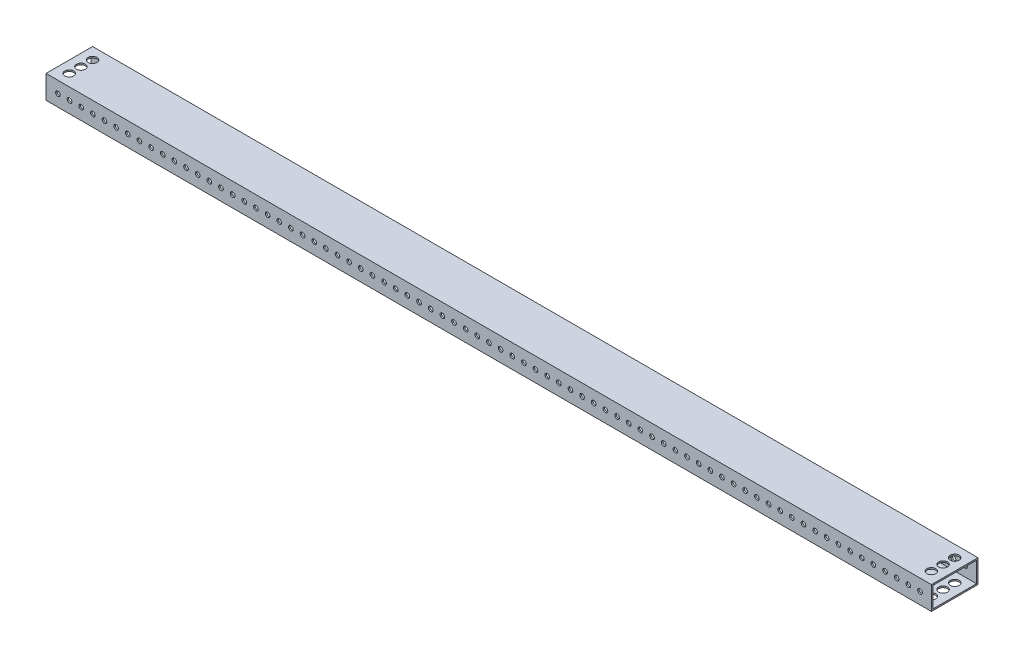
SolidWorks part; units mm, degrees
ref_plane "Front Plane" through (0, 0, 0) normal (0, 0, 1) x (1, 0, 0)
ref_plane "Top Plane" through (0, 0, 0) normal (0, 1, 0) x (1, 0, 0)
ref_plane "Right Plane" through (0, 0, 0) normal (1, 0, 0) x (0, 0, -1)
sketch "Sketch1" plane through (0, 0, 0) normal (0, 1, 0) x (1, 0, 0)
  line L1 (482.6, 25.4) -> (-482.6, 25.4)
  line L2 (482.6, 25.4) -> (482.6, -25.4)
  line L3 (482.6, -25.4) -> (-482.6, -25.4)
  line L4 (-482.6, 25.4) -> (-482.6, -25.4)
  line L5 (482.6, 25.4) -> (-482.6, -25.4) construction
  line L6 (482.6, -25.4) -> (-482.6, 25.4) construction
  point P0 (0, 0)
  dimension "D1" = 50.8
  dimension "D2" = 965.2
extrude "Boss-Extrude1" add sketch "Sketch1" along normal blind 25.4
sketch "Sketch2" plane through (-482.6, 0, 0) normal (-1, 0, 0) x (0, 0, 1)
  line L1 (23.7937, 23.7836) -> (-23.7836, 23.7836)
  line L2 (23.7937, 23.7836) -> (23.7937, 1.6265)
  line L3 (23.7937, 1.6265) -> (-23.7836, 1.6265)
  line L4 (-23.7836, 23.7836) -> (-23.7836, 1.6265)
  line L6 (-25.4, 25.4) -> (-25.4, 0) construction
  line L7 (25.4, 25.4) -> (25.4, 0) construction
  dimension "D1" = 2.286
  dimension "D2" = 2.286
  dimension "D3" = 1.6164
  dimension "D4" = 1.6063
extrude "Cut-Extrude1" cut sketch "Sketch2" against normal through all
sketch "Sketch3" plane through (0, 0, 25.4) normal (0, 0, 1) x (1, 0, 0)
  line L0 (-1393.7901, 12.7) -> (48606.2099, 12.7) construction
  line L1 (-482.6, 25.4) -> (-482.6, 0) construction
  circle A1 centre (-469.646, 12.7) radius 2.54
  circle A2 centre (-456.946, 12.7) radius 2.54
  circle A3 centre (-444.246, 12.7) radius 2.54
  circle A4 centre (-431.546, 12.7) radius 2.54
  circle A5 centre (-418.846, 12.7) radius 2.54
  circle A6 centre (-406.146, 12.7) radius 2.54
  circle A7 centre (-393.446, 12.7) radius 2.54
  circle A8 centre (-380.746, 12.7) radius 2.54
  circle A9 centre (-368.046, 12.7) radius 2.54
  circle A10 centre (-355.346, 12.7) radius 2.54
  circle A11 centre (-342.646, 12.7) radius 2.54
  circle A12 centre (-329.946, 12.7) radius 2.54
  circle A13 centre (-317.246, 12.7) radius 2.54
  circle A14 centre (-304.546, 12.7) radius 2.54
  circle A15 centre (-291.846, 12.7) radius 2.54
  circle A16 centre (-279.146, 12.7) radius 2.54
  circle A17 centre (-266.446, 12.7) radius 2.54
  circle A18 centre (-253.746, 12.7) radius 2.54
  circle A19 centre (-241.046, 12.7) radius 2.54
  circle A20 centre (-228.346, 12.7) radius 2.54
  circle A21 centre (-215.646, 12.7) radius 2.54
  circle A22 centre (-202.946, 12.7) radius 2.54
  circle A23 centre (-190.246, 12.7) radius 2.54
  circle A24 centre (-177.546, 12.7) radius 2.54
  circle A25 centre (-164.846, 12.7) radius 2.54
  circle A26 centre (-152.146, 12.7) radius 2.54
  circle A27 centre (-139.446, 12.7) radius 2.54
  circle A28 centre (-126.746, 12.7) radius 2.54
  circle A29 centre (-114.046, 12.7) radius 2.54
  circle A30 centre (-101.346, 12.7) radius 2.54
  circle A31 centre (-88.646, 12.7) radius 2.54
  circle A32 centre (-75.946, 12.7) radius 2.54
  circle A33 centre (-63.246, 12.7) radius 2.54
  circle A34 centre (-50.546, 12.7) radius 2.54
  circle A35 centre (-37.846, 12.7) radius 2.54
  circle A36 centre (-25.146, 12.7) radius 2.54
  circle A37 centre (-12.446, 12.7) radius 2.54
  circle A38 centre (0.254, 12.7) radius 2.54
  circle A39 centre (12.954, 12.7) radius 2.54
  circle A40 centre (25.654, 12.7) radius 2.54
  circle A41 centre (38.354, 12.7) radius 2.54
  circle A42 centre (51.054, 12.7) radius 2.54
  circle A43 centre (63.754, 12.7) radius 2.54
  circle A44 centre (76.454, 12.7) radius 2.54
  circle A45 centre (89.154, 12.7) radius 2.54
  circle A46 centre (101.854, 12.7) radius 2.54
  circle A47 centre (114.554, 12.7) radius 2.54
  circle A48 centre (127.254, 12.7) radius 2.54
  circle A49 centre (139.954, 12.7) radius 2.54
  circle A50 centre (152.654, 12.7) radius 2.54
  circle A51 centre (165.354, 12.7) radius 2.54
  circle A52 centre (178.054, 12.7) radius 2.54
  circle A53 centre (190.754, 12.7) radius 2.54
  circle A54 centre (203.454, 12.7) radius 2.54
  circle A55 centre (216.154, 12.7) radius 2.54
  circle A56 centre (228.854, 12.7) radius 2.54
  circle A57 centre (241.554, 12.7) radius 2.54
  circle A58 centre (254.254, 12.7) radius 2.54
  circle A59 centre (266.954, 12.7) radius 2.54
  circle A60 centre (279.654, 12.7) radius 2.54
  circle A61 centre (292.354, 12.7) radius 2.54
  circle A62 centre (305.054, 12.7) radius 2.54
  circle A63 centre (317.754, 12.7) radius 2.54
  circle A64 centre (330.454, 12.7) radius 2.54
  circle A65 centre (343.154, 12.7) radius 2.54
  circle A66 centre (355.854, 12.7) radius 2.54
  circle A67 centre (368.554, 12.7) radius 2.54
  circle A68 centre (381.254, 12.7) radius 2.54
  circle A69 centre (393.954, 12.7) radius 2.54
  circle A70 centre (406.654, 12.7) radius 2.54
  circle A71 centre (419.354, 12.7) radius 2.54
  circle A72 centre (432.054, 12.7) radius 2.54
  circle A73 centre (444.754, 12.7) radius 2.54
  circle A74 centre (457.454, 12.7) radius 2.54
  circle A75 centre (470.154, 12.7) radius 2.54
  point P5 (-482.6, 12.7)
  dimension "D1" = 5.08
  dimension "D2" = 12.954
  dimension "D4" = 12.7
  dimension "D5" = 16
  dimension "D3" = 60
extrude "Cut-Extrude2" cut sketch "Sketch3" against normal through all
sketch "Sketch4" plane through (0, 25.4, 0) normal (0, 1, 0) x (1, 0, 0)
  line L0 (-1393.7901, 0) -> (48606.2099, 0) construction
  line L1 (-482.6, 25.4) -> (-482.6, -25.4) construction
  line L2 (-1388.247, 12.7) -> (48611.753, 12.7) construction
  line L3 (-1379.4121, -12.7) -> (48620.5879, -12.7) construction
  line L4 (-482.6, -25.4) -> (482.6, -25.4) construction
  line L5 (0, 25.4) -> (0, -25.4) construction
  line L6 (482.6, 25.4) -> (-482.6, 25.4) construction
  circle A0 centre (-469.9, 12.7) radius 4.826
  circle A2 centre (-469.9, -12.7) radius 4.826
  circle A3 centre (-469.9, 0) radius 4.826
  circle A4 centre (469.9, 12.7) radius 4.826
  circle A5 centre (469.9, 0) radius 4.826
  circle A6 centre (469.9, -12.7) radius 4.826
  point P5 (-482.6, 0)
  dimension "D1" = 9.652
  dimension "D5" = 12.7
  dimension "D6" = 9.652
  dimension "D2" = 12.7
  dimension "D3" = 12.7
  dimension "D4" = 12.7
extrude "Cut-Extrude3" cut sketch "Sketch4" against normal through all
